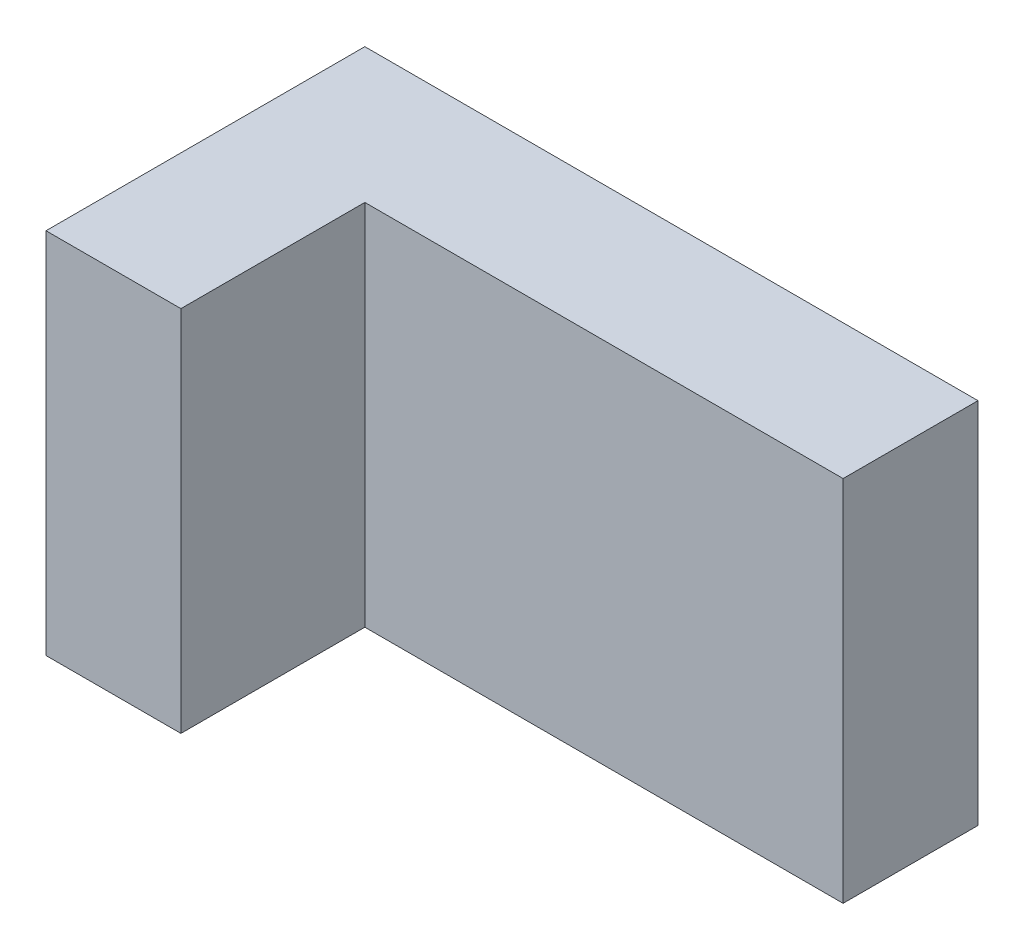
SolidWorks part; units mm, degrees
ref_plane "Front Plane" through (0, 0, 0) normal (0, 0, 1) x (1, 0, 0)
ref_plane "Top Plane" through (0, 0, 0) normal (0, 1, 0) x (1, 0, 0)
ref_plane "Right Plane" through (0, 0, 0) normal (1, 0, 0) x (0, 0, -1)
sketch "Sketch1" plane through (0, 0, 0) normal (0, 0, 1) x (1, 0, 0)
  line L1 (-27.4104, 17.6385) -> (-17.4104, 17.6385)
  line L2 (-27.4104, 17.6385) -> (-27.4104, 11.6385)
  line L3 (-27.4104, 11.6385) -> (-17.4104, 11.6385)
  line L4 (-17.4104, 17.6385) -> (-17.4104, 11.6385)
  dimension "D1" = 6
  dimension "1" = 10
extrude "Boss-Extrude1" add sketch "Sketch1" along normal blind 2.2
sketch "Sketch2" plane through (0, 0, 2.2) normal (0, 0, 1) x (1, 0, 0)
  line L0 (-27.4104, 11.6385) -> (-17.4104, 11.6385) construction
  line L1 (-27.4104, 17.6385) -> (-25.2104, 17.6385)
  line L2 (-27.4104, 17.6385) -> (-27.4104, 11.6385)
  line L3 (-27.4104, 11.6385) -> (-25.2104, 11.6385)
  line L4 (-25.2104, 17.6385) -> (-25.2104, 11.6385)
  dimension "D1" = 2.2
extrude "Boss-Extrude2" add sketch "Sketch2" along normal blind 3
